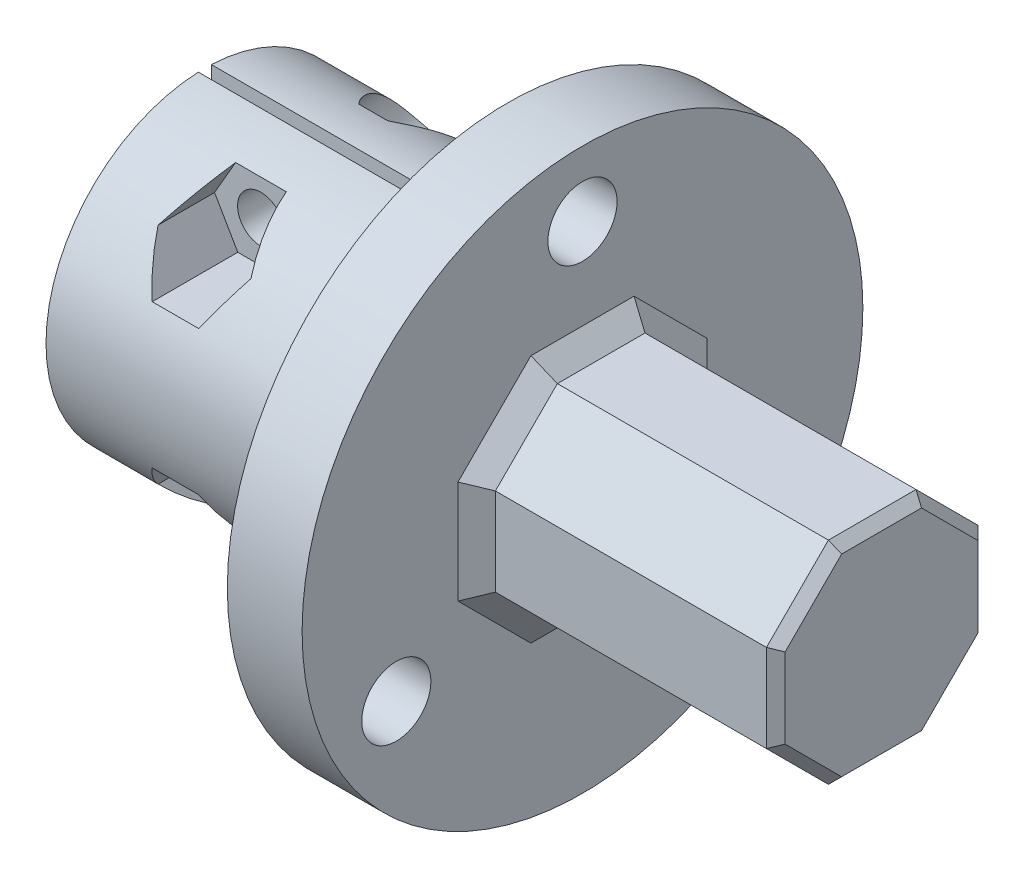
SolidWorks part; units mm, degrees
ref_plane "Front Plane" through (0, 0, 0) normal (0, 0, 1) x (1, 0, 0)
ref_plane "Top Plane" through (0, 0, 0) normal (0, 1, 0) x (1, 0, 0)
ref_plane "Right Plane" through (0, 0, 0) normal (1, 0, 0) x (0, 0, -1)
sketch "Sketch1" plane through (0, 0, 0) normal (1, 0, 0) x (0, 0, -1)
  line L0 (2.4, 1.8822) -> (2.4, -1.8822)
  line L1 (-3.05, 3.0797) -> (-3.05, -3.0797) construction
  circle A0 centre (0, 0) radius 8.5
  arc A1 (2.4, 1.8822) -> (2.4, -1.8822) centre (0, 0) ccw
  point P8 (-3.05, 0)
  dimension "D1" = 17
  dimension "D2" = 3.05
  dimension "D3" = 5.45
extrude "Boss-Extrude1" add sketch "Sketch1" along normal blind 16.2
sketch "Sketch4" plane through (0, 0, 0) normal (-1, 0, 0) x (0, 0, 1)
  line L1 (-0.35, -8.5) -> (0.35, -8.5)
  line L2 (-0.35, -8.5) -> (-0.35, 8.5)
  line L3 (-0.35, 8.5) -> (0.35, 8.5)
  line L4 (0.35, -8.5) -> (0.35, 8.5)
  line L5 (-0.35, -8.5) -> (0.35, 8.5) construction
  line L6 (-0.35, 8.5) -> (0.35, -8.5) construction
  circle A0 centre (0, 0) radius 8.5 construction
  point P0 (0, 0)
  dimension "D1" = 0.7
extrude "Cut-Extrude2" cut sketch "Sketch4" against normal through all
sketch "Sketch5" plane through (16.2, 0, 0) normal (1, 0, 0) x (0, 0, -1)
  circle A0 centre (0, 0) radius 15
  dimension "D1" = 30
extrude "Boss-Extrude2" add sketch "Sketch5" along normal blind 4
sketch "Sketch6" plane through (20.2, 0, 0) normal (1, 0, 0) x (0, 0, -1)
  line L0 (-5.6588, -2.3439) -> (5.6588, 2.3439) construction
  line L1 (2.3439, 5.6588) -> (-2.3439, 5.6588)
  line L2 (-2.3439, 5.6588) -> (-5.6588, 2.3439)
  line L3 (-5.6588, 2.3439) -> (-5.6588, -2.3439)
  line L4 (-5.6588, -2.3439) -> (-2.3439, -5.6588)
  line L5 (-2.3439, -5.6588) -> (2.3439, -5.6588)
  line L6 (2.3439, -5.6588) -> (5.6588, -2.3439)
  line L7 (5.6588, -2.3439) -> (5.6588, 2.3439)
  line L8 (5.6588, 2.3439) -> (2.3439, 5.6588)
  circle A0 centre (0, 0) radius 5.6588 construction
  dimension "D1" = 12.25
extrude "Boss-Extrude3" add sketch "Sketch6" along normal blind 16
sketch "Sketch7" plane through (20.2, 0, 0) normal (1, 0, 0) x (0, 0, -1)
  line L0 (0, 11.5) -> (0, 0) construction
  line L1 (0, 0) -> (-9.9593, -5.75) construction
  line L2 (0, 0) -> (9.9593, -5.75) construction
  circle A0 centre (0, 0) radius 11.5 construction
  circle A1 centre (0, 11.5) radius 1.85
  circle A2 centre (-9.9593, -5.75) radius 1.85
  circle A3 centre (9.9593, -5.75) radius 1.85
  dimension "D3" = 23
  dimension "D4" = 3.7
  dimension "D1" = 120
  dimension "D2" = 120
extrude "Cut-Extrude3" cut sketch "Sketch7" against normal through all
chamfer "Chamfer1" distance 0.5 angle 45 8 edges at (36.2, 0, -5.6588) (36.2, -4.0013, -4.0013) (36.2, -5.6588, 0) (36.2, -4.0013, 4.0013) (36.2, 0, 5.6588) (36.2, 4.0013, 4.0013) (36.2, 5.6588, 0) (36.2, 4.0013, -4.0013)
sketch "Sketch8" plane through (0, 0, 0) normal (0, 0, 1) x (1, 0, 0)
  line L0 (6, 8.4928) -> (6, -8.4928) construction
  line L1 (16.2, 8.4928) -> (0, 8.4928) construction
  line L2 (0, -8.4928) -> (16.2, -8.4928) construction
  line L3 (0, 0) -> (15.1112, 0) construction
  line L4 (0, 8.4928) -> (0, -8.4928) construction
  line L5 (6, -6) -> (6, 6) construction
  circle A0 centre (6, 6) radius 1.25
  circle A1 centre (6, -6) radius 1.25
  point P18 (6, 0)
  dimension "D1" = 2.5
  dimension "D2" = 12
  dimension "D4" = 6
extrude "Cut-Extrude4" cut sketch "Sketch8" against normal through all both and the other way through all
ref_plane "Plane1" through (0, 0, 3) normal (0, 0, 1) x (1, 0, 0)
sketch "Sketch9" plane through (0, 0, 3) normal (0, 0, 1) x (1, 0, 0)
  line L1 (7.2413, 3.85) -> (8.4826, 6)
  line L2 (8.4826, 6) -> (7.2413, 8.15)
  line L3 (7.2413, 8.15) -> (4.7587, 8.15)
  line L4 (4.7587, 8.15) -> (3.5174, 6)
  line L5 (3.5174, 6) -> (4.7587, 3.85)
  line L6 (4.7587, 3.85) -> (7.2413, 3.85)
  line L7 (7.2413, -8.15) -> (8.4826, -6)
  line L8 (8.4826, -6) -> (7.2413, -3.85)
  line L9 (7.2413, -3.85) -> (4.7587, -3.85)
  line L10 (4.7587, -3.85) -> (3.5174, -6)
  line L11 (3.5174, -6) -> (4.7587, -8.15)
  line L12 (4.7587, -8.15) -> (7.2413, -8.15)
  circle A0 centre (6, 6) radius 2.15 construction
  circle A1 centre (6, -6) radius 2.15 construction
  circle A4 centre (6, -6) radius 1.25 construction
  dimension "D1" = 4.3
extrude "Cut-Extrude5" cut sketch "Sketch9" along normal through all
ref_plane "Plane2" through (0, 0, -3) normal (0, 0, 1) x (1, 0, 0)
sketch "Sketch10" plane through (0, 0, -3) normal (0, 0, 1) x (1, 0, 0)
  circle A0 centre (6, 6) radius 2.1
  circle A1 centre (6, -6) radius 2.1
  dimension "D1" = 4.2
extrude "Cut-Extrude6" cut sketch "Sketch10" against normal through all
sketch "Sketch11" plane through (16.2, 0, 0) normal (-1, 0, 0) x (0, 0, 1)
  circle A0 centre (-9.9593, -5.75) radius 2.7
  dimension "D1" = 5.4
fillet "Fillet1" radius 0.5 2 edges at (16.2, 0, 8.5) (16.2, 0, -8.5)
chamfer "Chamfer2" distance 1 angle 45 8 edges at (20.2, 4.0013, 4.0013) (20.2, 5.6588, 0) (20.2, 4.0013, -4.0013) (20.2, 0, -5.6588) (20.2, -4.0013, -4.0013) (20.2, -5.6588, 0) (20.2, 0, 5.6588) (20.2, -4.0013, 4.0013)
